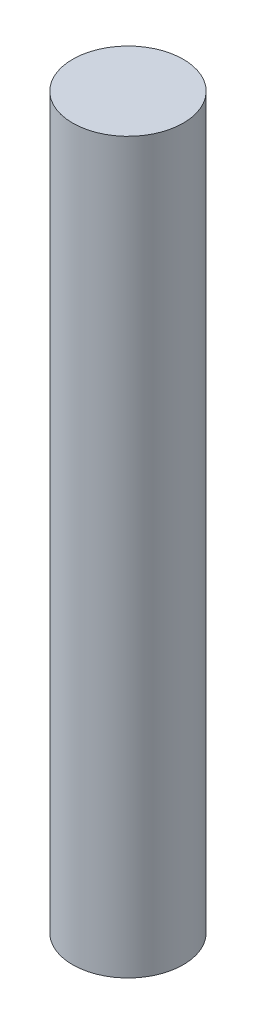
SolidWorks part; units mm, degrees
ref_plane "Front Plane" through (0, 0, 0) normal (0, 0, 1) x (1, 0, 0)
ref_plane "Top Plane" through (0, 0, 0) normal (0, 1, 0) x (1, 0, 0)
ref_plane "Right Plane" through (0, 0, 0) normal (1, 0, 0) x (0, 0, -1)
sketch "Sketch1" plane through (0, 0, 0) normal (0, 1, 0) x (1, 0, 0)
  circle A0 centre (0, 0) radius 10.795
  dimension "D1" = 21.59
extrude "Boss-Extrude1" add sketch "Sketch1" along normal blind 142.24
